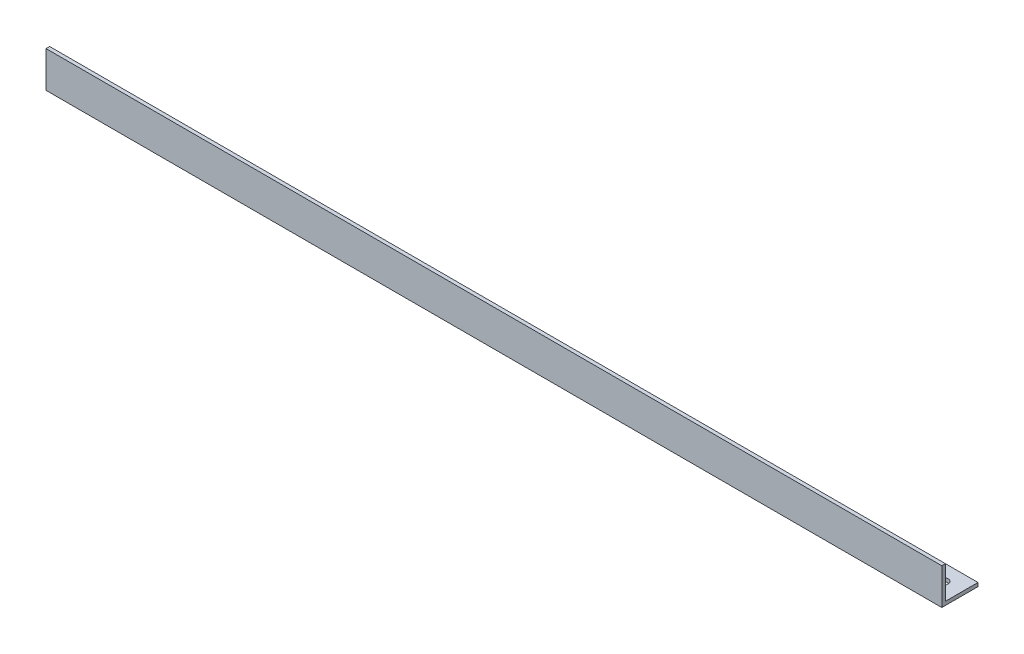
SolidWorks part; units mm, degrees
ref_plane "Front Plane" through (0, 0, 0) normal (0, 0, 1) x (1, 0, 0)
ref_plane "Top Plane" through (0, 0, 0) normal (0, 1, 0) x (1, 0, 0)
ref_plane "Right Plane" through (0, 0, 0) normal (1, 0, 0) x (0, 0, -1)
sketch "Sketch1" plane through (0, 0, 0) normal (1, 0, 0) x (0, 0, -1)
  line L0 (0, 20) -> (0, 0)
  line L1 (0, 0) -> (20, 0)
  line L2 (20, 0) -> (20, 2)
  line L3 (20, 2) -> (2, 2)
  line L4 (2, 2) -> (2, 20)
  line L5 (2, 20) -> (0, 20)
  dimension "D1" = 20
  dimension "D2" = 20
  dimension "D3" = 2
  dimension "D4" = 2
extrude "Boss-Extrude1" add sketch "Sketch1" along normal blind 325 and the other way blind 170
sketch "Sketch2" plane through (0, 2, 0) normal (0, 1, 0) x (1, 0, 0)
  line L0 (-170, 0) -> (325, 0) construction
  line L1 (325, 20) -> (325, 2) construction
  line L2 (-170, 20) -> (325, 20) construction
  line L3 (-170, 20) -> (-170, 2) construction
  circle A0 centre (0, 9.8) radius 2.95
  circle A1 centre (315, 11) radius 2.5
  circle A2 centre (-160, 11) radius 2.5
  dimension "D2" = 5.9
  dimension "D5" = 5
  dimension "D8" = 5
  dimension "D1" = 9.8
  dimension "D3" = 10
  dimension "D4" = 9
  dimension "D6" = 10
  dimension "D7" = 9
extrude "Cut-Extrude1" cut sketch "Sketch2" against normal blind 2
